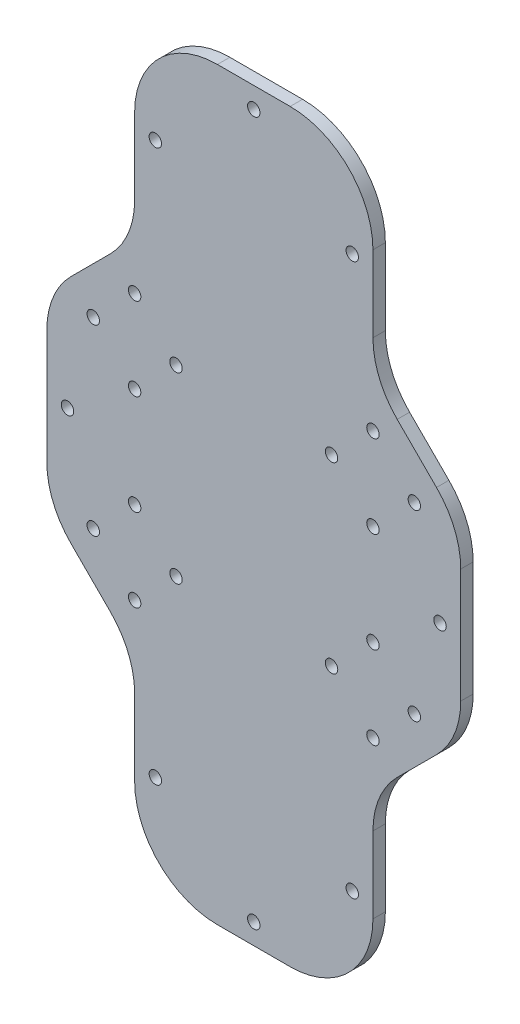
SolidWorks part; units mm, degrees
ref_plane "Front Plane" through (0, 0, 0) normal (0, 0, 1) x (1, 0, 0)
ref_plane "Top Plane" through (0, 0, 0) normal (0, 1, 0) x (1, 0, 0)
ref_plane "Right Plane" through (0, 0, 0) normal (1, 0, 0) x (0, 0, -1)
sketch "Sketch2" plane through (0, 0, 0) normal (0, 0, 1) x (1, 0, 0)
  line L5 (-74.6649, 375.0558) -> (424.0017, 375.0558) construction
  line L32 (0, -777.1069) -> (0, 1023.1798) construction
  line L33 (-581.0456, 0) -> (767.9363, 0) construction
  line L34 (-50, -13.8157) -> (-50, 13.8157)
  line L36 (-28.7868, 51.5975) -> (-28.7868, 70)
  line L37 (-8.7868, 90) -> (8.7868, 90)
  line L38 (28.7868, 51.5975) -> (28.7868, 70)
  line L39 (44.1421, 27.9579) -> (34.6447, 37.4553)
  line L40 (50, -13.8157) -> (50, 13.8157)
  line L41 (44.1421, -27.9579) -> (34.6447, -37.4553)
  line L42 (28.7868, -51.5975) -> (28.7868, -70)
  line L43 (-8.7868, -90) -> (8.7868, -90)
  line L44 (-28.7868, -51.5975) -> (-28.7868, -70)
  line L45 (-44.1421, -27.9579) -> (-34.6447, -37.4553)
  line L48 (-44.1421, 27.9579) -> (-34.6447, 37.4553)
  line L49 (-28.7868, 43.3132) -> (-28.7868, -15.605) construction
  line L50 (-50, 22.1) -> (17.0094, 22.1) construction
  circle A0 centre (0, 85) radius 1.5
  circle A1 centre (-23.7868, 66.6566) radius 1.5
  circle A3 centre (-28.7868, 32.1) radius 1.5
  circle A4 centre (-38.7868, 22.1) radius 1.5
  circle A5 centre (-28.7868, 12.1) radius 1.5
  circle A6 centre (-18.7868, 22.1) radius 1.5
  circle A7 centre (-45, 0) radius 1.5
  circle A8 centre (45, 0) radius 1.5
  circle A9 centre (18.7868, 22.1) radius 1.5
  circle A10 centre (28.7868, 12.1) radius 1.5
  circle A11 centre (38.7868, 22.1) radius 1.5
  circle A12 centre (28.7868, 32.1) radius 1.5
  circle A13 centre (23.7868, 66.6566) radius 1.5
  circle A14 centre (28.7868, -32.1) radius 1.5
  circle A15 centre (38.7868, -22.1) radius 1.5
  circle A16 centre (28.7868, -12.1) radius 1.5
  circle A17 centre (18.7868, -22.1) radius 1.5
  circle A18 centre (-18.7868, -22.1) radius 1.5
  circle A19 centre (-28.7868, -12.1) radius 1.5
  circle A20 centre (-38.7868, -22.1) radius 1.5
  circle A21 centre (-28.7868, -32.1) radius 1.5
  circle A22 centre (23.7868, -66.6566) radius 1.5
  circle A23 centre (-23.7868, -66.6566) radius 1.5
  circle A24 centre (0, -85) radius 1.5
  arc A25 (34.6447, 37.4553) -> (28.7868, 51.5975) centre (48.7868, 51.5975) cw
  arc A26 (44.1421, 27.9579) -> (50, 13.8157) centre (30, 13.8157) cw
  arc A27 (50, -13.8157) -> (44.1421, -27.9579) centre (30, -13.8157) cw
  arc A28 (28.7868, -51.5975) -> (34.6447, -37.4553) centre (48.7868, -51.5975) cw
  arc A29 (28.7868, -70) -> (8.7868, -90) centre (8.7868, -70) cw
  arc A30 (-8.7868, -90) -> (-28.7868, -70) centre (-8.7868, -70) cw
  arc A31 (-28.7868, -51.5975) -> (-34.6447, -37.4553) centre (-48.7868, -51.5975) ccw
  arc A32 (-44.1421, -27.9579) -> (-50, -13.8157) centre (-30, -13.8157) cw
  arc A33 (-50, 13.8157) -> (-44.1421, 27.9579) centre (-30, 13.8157) cw
  arc A34 (-34.6447, 37.4553) -> (-28.7868, 51.5975) centre (-48.7868, 51.5975) ccw
  arc A35 (28.7868, 70) -> (8.7868, 90) centre (8.7868, 70) ccw
  arc A36 (-28.7868, 70) -> (-8.7868, 90) centre (-8.7868, 70) cw
  point P6 (0, -90)
  point P14 (0, 90)
  point P18 (50, 0)
  point P24 (-50, 0)
  point P75 (28.7868, 43.3132)
  point P78 (50, 22.1)
  point P81 (50, -22.1)
  point P84 (28.7868, -43.3132)
  point P87 (28.7868, -90)
  point P90 (-28.7868, -90)
  point P93 (-28.7868, -43.3132)
  point P96 (-50, -22.1)
  point P105 (28.7868, 90)
  point P108 (-28.7868, 90)
  dimension "D5" = 5
  dimension "D6" = 20
  dimension "D7" = 5
  dimension "D1" = 50
  dimension "D2" = 22.1
  dimension "D3" = 30
  dimension "D4" = 90
extrude "Boss-Extrude2" add sketch "Sketch2" along normal blind 3
